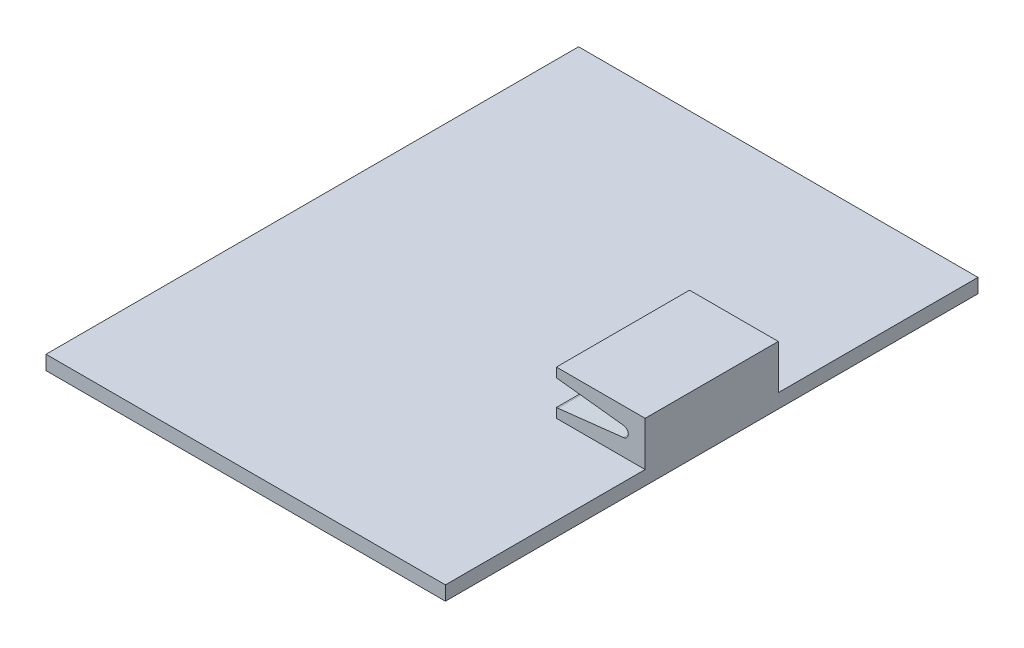
SolidWorks part; units mm, degrees
ref_plane "Front Plane" through (0, 0, 0) normal (0, 0, 1) x (1, 0, 0)
ref_plane "Top Plane" through (0, 0, 0) normal (0, 1, 0) x (1, 0, 0)
ref_plane "Right Plane" through (0, 0, 0) normal (1, 0, 0) x (0, 0, -1)
sketch "Sketch1" plane through (0, 0, 0) normal (0, 1, 0) x (1, 0, 0)
  line L1 (-225, -300) -> (225, -300)
  line L2 (-225, -300) -> (-225, 300)
  line L3 (-225, 300) -> (225, 300)
  line L4 (225, -300) -> (225, 300)
  line L5 (-225, -300) -> (225, 300) construction
  line L6 (-225, 300) -> (225, -300) construction
  point P0 (0, 0)
  dimension "D1" = 600
  dimension "D2" = 450
extrude "Boss-Extrude1" add sketch "Sketch1" along normal blind 16 contours L2 L3 L4 L1
sketch "Sketch2" plane through (0, 16, 0) normal (0, 1, 0) x (1, 0, 0)
  line L0 (-225, 0) -> (175, 0) construction
  line L1 (-225, -300) -> (-225, 300) construction
  line L2 (225, -300) -> (225, 300) construction
  line L3 (125, 75) -> (225, 75)
  line L4 (125, 75) -> (125, -75)
  line L5 (125, -75) -> (225, -75)
  line L6 (225, 75) -> (225, -75)
  line L7 (125, 75) -> (225, -75) construction
  line L8 (125, -75) -> (225, 75) construction
  point P9 (225, 0)
  dimension "D1" = 100
  dimension "D2" = 150
extrude "Boss-Extrude2" add sketch "Sketch2" along normal blind 50
sketch "Sketch3" plane through (0, 0, -75) normal (0, 0, -1) x (-1, 0, 0)
  line L0 (-125, 66) -> (-125, 16) construction
  line L1 (-225, 66) -> (-225, 16) construction
  line L2 (-225, 41) -> (-125, 41) construction
  line L3 (-200.6743, 46.962) -> (-126.6217, 55.3379)
  line L4 (-200.6743, 35.038) -> (-126.6217, 26.6621)
  arc A0 (-200.6743, 46.962) -> (-200.6743, 35.038) centre (-200, 41) ccw
  arc A1 (-126.6217, 26.6621) -> (-126.6217, 55.3379) centre (-125, 41) ccw
  point P3 (-125, 41)
  dimension "D1" = 25
extrude "Cut-Extrude1" cut sketch "Sketch3" against normal through all both and the other way through all
